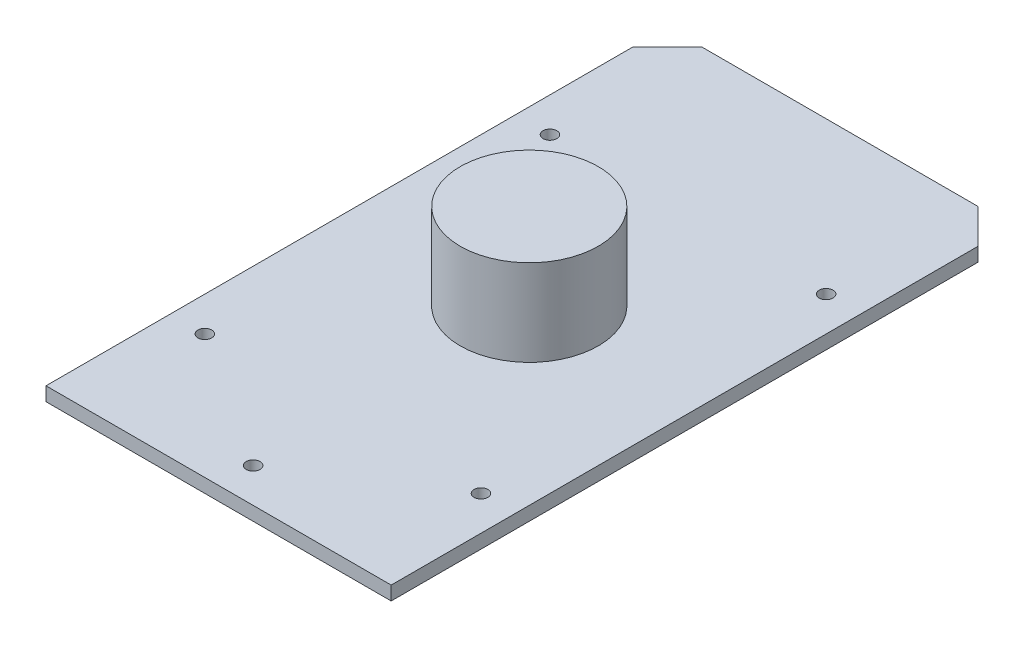
SolidWorks part; units mm, degrees
ref_plane "Front Plane" through (0, 0, 0) normal (0, 0, 1) x (1, 0, 0)
ref_plane "Top Plane" through (0, 0, 0) normal (0, 1, 0) x (1, 0, 0)
ref_plane "Right Plane" through (0, 0, 0) normal (1, 0, 0) x (0, 0, -1)
sketch "Sketch1" plane through (0, 0, 0) normal (0, 1, 0) x (1, 0, 0)
  line L1 (-250, 450) -> (250, 450)
  line L2 (-250, 450) -> (-250, -450)
  line L3 (-250, -450) -> (250, -450)
  line L4 (250, 450) -> (250, -450)
  line L5 (-250, 450) -> (250, -450) construction
  line L6 (-250, -450) -> (250, 450) construction
  point P0 (0, 0)
  dimension "D1" = 900
  dimension "D2" = 500
extrude "Boss-Extrude1" add sketch "Sketch1" along normal blind 20
chamfer "Chamfer1" distance 50 angle 45 2 edges at (-250, 10, -450) (250, 10, -450)
sketch "Sketch2" plane through (0, 20, 0) normal (0, 1, 0) x (1, 0, 0)
  line L0 (0, 450) -> (0, -450) construction
  line L1 (200, 450) -> (-200, 450) construction
  line L2 (-250, -450) -> (250, -450) construction
  line L3 (250, -450) -> (250, 400) construction
  line L4 (-200, -270) -> (200, -270) construction
  line L5 (-200, -270) -> (-200, 230) construction
  line L6 (-200, 230) -> (200, 230) construction
  line L7 (200, -270) -> (200, 230) construction
  line L8 (-200, -270) -> (200, 230) construction
  line L9 (-200, 230) -> (200, -270) construction
  circle A0 centre (200, 230) radius 10
  circle A1 centre (-200, 230) radius 10
  circle A2 centre (200, -270) radius 10
  circle A3 centre (-200, -270) radius 10
  point P6 (0, -20)
  dimension "D4" = 20
  dimension "D1" = 20
  dimension "D2" = 50
  dimension "D3" = 500
extrude "Cut-Extrude1" cut sketch "Sketch2" against normal through all
sketch "Sketch3" plane through (0, 20, 0) normal (0, 1, 0) x (1, 0, 0)
  circle A0 centre (0, 0) radius 100
  dimension "D1" = 200
extrude "Boss-Extrude2" add sketch "Sketch3" along normal blind 125
sketch "Sketch4" plane through (0, 20, 0) normal (0, 1, 0) x (1, 0, 0)
  line L0 (0, 0) -> (0, -450) construction
  line L1 (-250, -450) -> (250, -450) construction
  circle A0 centre (0, -400) radius 10
  circle A1 centre (200, -270) radius 10 construction
  dimension "D1" = 50
extrude "Cut-Extrude2" cut sketch "Sketch4" against normal through all
